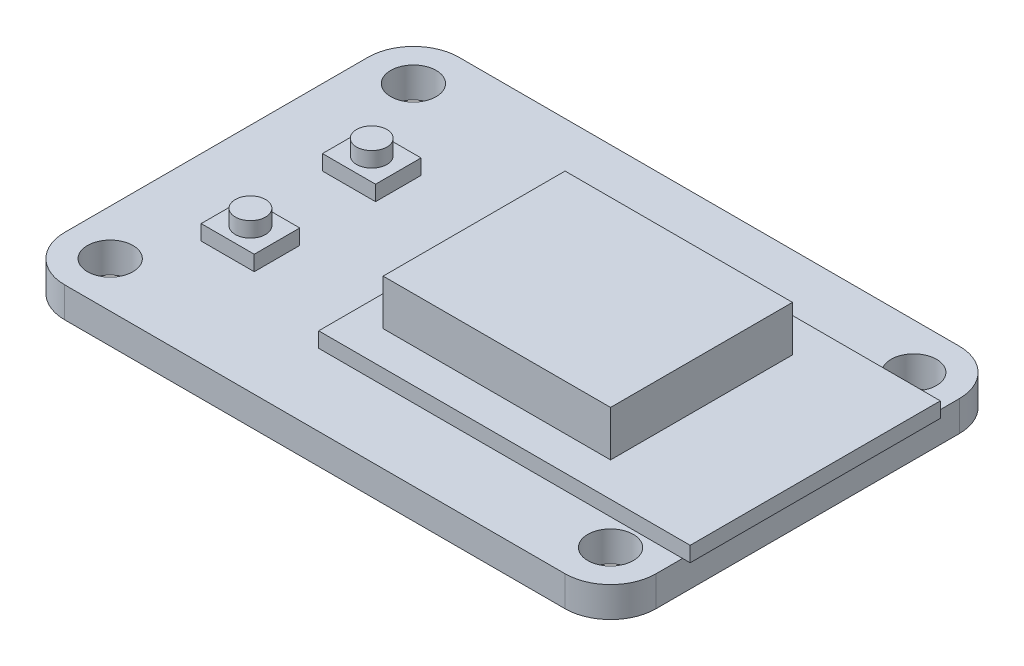
SolidWorks part; units mm, degrees
ref_plane "Front Plane" through (0, 0, 0) normal (0, 0, 1) x (1, 0, 0)
ref_plane "Top Plane" through (0, 0, 0) normal (0, 1, 0) x (1, 0, 0)
ref_plane "Right Plane" through (0, 0, 0) normal (1, 0, 0) x (0, 0, -1)
sketch "Sketch1" plane through (0, 0, 0) normal (0, 1, 0) x (1, 0, 0)
  line L1 (-19.5, 13) -> (19.5, 13)
  line L2 (-19.5, 13) -> (-19.5, -13)
  line L3 (-19.5, -13) -> (19.5, -13)
  line L4 (19.5, 13) -> (19.5, -13)
  line L5 (-19.5, 13) -> (19.5, -13) construction
  line L6 (-19.5, -13) -> (19.5, 13) construction
  point P0 (0, 0)
  dimension "D1" = 26
  dimension "D2" = 39
extrude "Boss-Extrude1" add sketch "Sketch1" along normal blind 2
sketch "Sketch2" plane through (0, 2, 0) normal (0, 1, 0) x (1, 0, 0)
  line L0 (-19.5, -13) -> (19.5, -13) construction
  line L1 (-19.5, 13) -> (-19.5, -13) construction
  line L2 (19.5, 13) -> (-19.5, 13) construction
  line L3 (19.5, -13) -> (19.5, 13) construction
  circle A0 centre (-16.5, 10) radius 1.5
  circle A1 centre (-16.5, -10) radius 1.5
  circle A2 centre (16.5, -10) radius 1.5
  circle A3 centre (16.5, 10) radius 1.5
  dimension "D1" = 3
  dimension "D2" = 3
  dimension "D3" = 3
  dimension "D4" = 3
  dimension "D5" = 3
  dimension "D6" = 3
  dimension "D7" = 3
  dimension "D9" = 3
  dimension "D11" = 3
  dimension "D8" = 3
  dimension "D10" = 3
  dimension "D12" = 3
extrude "Cut-Extrude1" cut sketch "Sketch2" against normal through all
sketch "Sketch3" plane through (0, 2, 0) normal (0, 1, 0) x (1, 0, 0)
  line L1 (-4.5, 8.25) -> (20, 8.25)
  line L2 (-4.5, 8.25) -> (-4.5, -8.25)
  line L3 (-4.5, -8.25) -> (20, -8.25)
  line L4 (20, 8.25) -> (20, -8.25)
  line L5 (-4.5, 8.25) -> (20, -8.25) construction
  line L6 (-4.5, -8.25) -> (20, 8.25) construction
  line L7 (-19.5, 13) -> (-19.5, -13) construction
  point P0 (7.75, 0)
  dimension "D1" = 16.5
  dimension "D2" = 0
  dimension "D3" = 24.5
  dimension "D4" = 15
extrude "Boss-Extrude2" add sketch "Sketch3" along normal blind 1
sketch "Sketch4" plane through (0, 3, 0) normal (0, 1, 0) x (1, 0, 0)
  line L0 (-4.5, -8.25) -> (20, -8.25) construction
  line L1 (-2.5, 6) -> (12.5, 6)
  line L2 (-2.5, 6) -> (-2.5, -6)
  line L3 (-2.5, -6) -> (12.5, -6)
  line L4 (12.5, 6) -> (12.5, -6)
  line L5 (-2.5, 6) -> (12.5, -6) construction
  line L6 (-2.5, -6) -> (12.5, 6) construction
  line L9 (-4.5, 8.25) -> (-4.5, -8.25) construction
  point P0 (5, 0)
  dimension "D1" = 12
  dimension "D2" = 15
  dimension "D3" = 2.25
  dimension "D4" = 2
extrude "Boss-Extrude3" add sketch "Sketch4" along normal blind 3
sketch "Sketch5" plane through (0, 2, 0) normal (0, 1, 0) x (1, 0, 0)
  line L0 (-19.5, 13) -> (-19.5, -13) construction
  line L1 (-14.5, 5) -> (-11, 5)
  line L2 (-14.5, 5) -> (-14.5, 2)
  line L3 (-14.5, 2) -> (-11, 2)
  line L4 (-11, 5) -> (-11, 2)
  line L5 (-14.5, 5) -> (-11, 2) construction
  line L6 (-14.5, 2) -> (-11, 5) construction
  line L7 (-14.5, -3) -> (-11, -3)
  line L8 (-14.5, -3) -> (-14.5, -6)
  line L9 (-14.5, -6) -> (-11, -6)
  line L10 (-11, -3) -> (-11, -6)
  line L11 (-14.5, -3) -> (-11, -6) construction
  line L12 (-14.5, -6) -> (-11, -3) construction
  line L13 (-19.5, -13) -> (19.5, -13) construction
  line L14 (19.5, 13) -> (-19.5, 13) construction
  point P0 (-12.75, 3.5)
  point P5 (-12.75, -4.5)
  dimension "D1" = 3
  dimension "D2" = 3
  dimension "D3" = 3.5
  dimension "D4" = 3.5
  dimension "D5" = 5
  dimension "D6" = 5
  dimension "D7" = 7
  dimension "D8" = 8
extrude "Boss-Extrude4" add sketch "Sketch5" along normal blind 1
sketch "Sketch6" plane through (0, 3, 0) normal (0, 1, 0) x (1, 0, 0)
  line L0 (-14.5, 2) -> (-11, 2) construction
  line L1 (-14.5, 5) -> (-14.5, 2) construction
  line L2 (-14.5, -3) -> (-14.5, -6) construction
  line L3 (-11, -3) -> (-14.5, -3) construction
  circle A0 centre (-12.75, 3.5) radius 1
  circle A1 centre (-12.75, -4.5) radius 1
  dimension "D1" = 2
  dimension "D2" = 2
  dimension "D3" = 1.5
  dimension "D5" = 1.75
  dimension "D6" = 1.5
  dimension "D4" = 1.75
extrude "Boss-Extrude5" add sketch "Sketch6" along normal blind 1
fillet "Fillet1" radius 3 4 edges at (19.5, 1, -13) (19.5, 1, 13) (-19.5, 1, -13) (-19.5, 1, 13)
